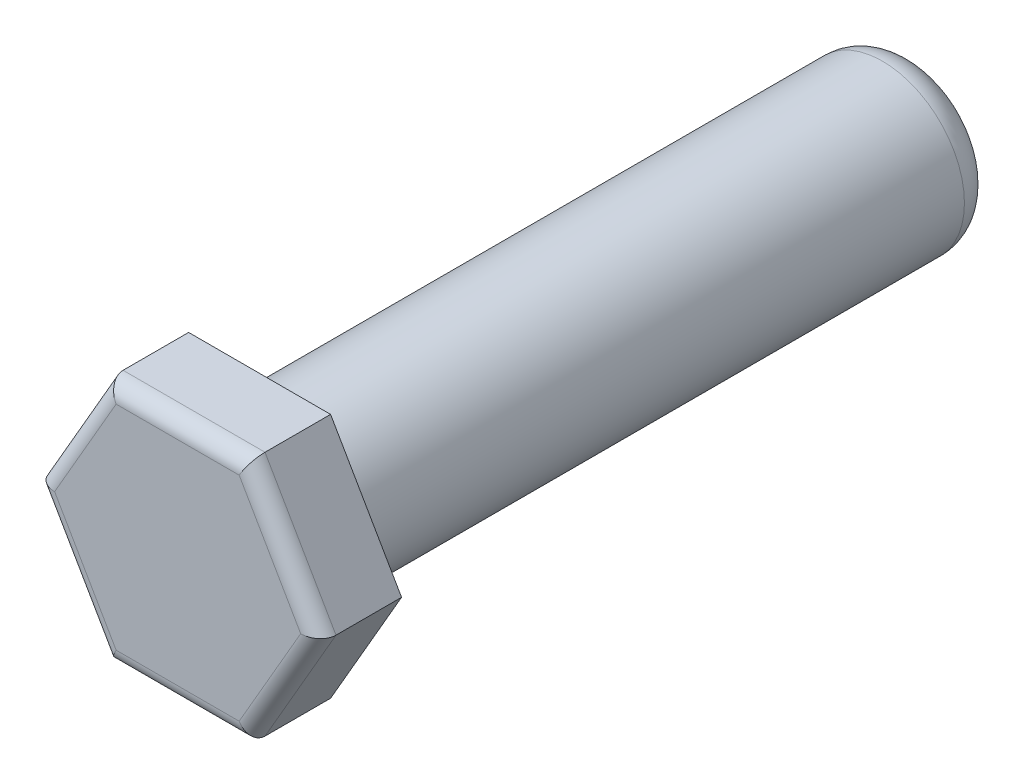
SolidWorks part; units mm, degrees
ref_plane "前视基准面" through (0, 0, 0) normal (0, 0, 1) x (1, 0, 0)
ref_plane "上视基准面" through (0, 0, 0) normal (0, 1, 0) x (1, 0, 0)
ref_plane "右视基准面" through (0, 0, 0) normal (1, 0, 0) x (0, 0, -1)
sketch "草图1" plane through (0, 0, 0) normal (0, 0, 1) x (1, 0, 0)
  circle A0 centre (0, 0) radius 5
  dimension "D1" = 10
extrude "凸台-拉伸1" add sketch "草图1" along normal blind 40
sketch "草图2" plane through (0, 0, 40) normal (0, 0, 1) x (1, 0, 0)
  line L1 (4.3301, -7.5) -> (8.6603, 0)
  line L2 (8.6603, 0) -> (4.3301, 7.5)
  line L3 (4.3301, 7.5) -> (-4.3301, 7.5)
  line L4 (-4.3301, 7.5) -> (-8.6603, 0)
  line L5 (-8.6603, 0) -> (-4.3301, -7.5)
  line L6 (-4.3301, -7.5) -> (4.3301, -7.5)
  circle A0 centre (0, 0) radius 7.5 construction
  dimension "D1" = 15
extrude "凸台-拉伸2" add sketch "草图2" along normal blind 5
fillet "圆角1" radius 1 6 edges at (6.4952, 3.75, 45) (6.4952, -3.75, 45) (0, -7.5, 45) (-6.4952, -3.75, 45) (-6.4952, 3.75, 45) (0, 7.5, 45)
fillet "圆角2" radius 2 1 edges at (5, 0, 0)
